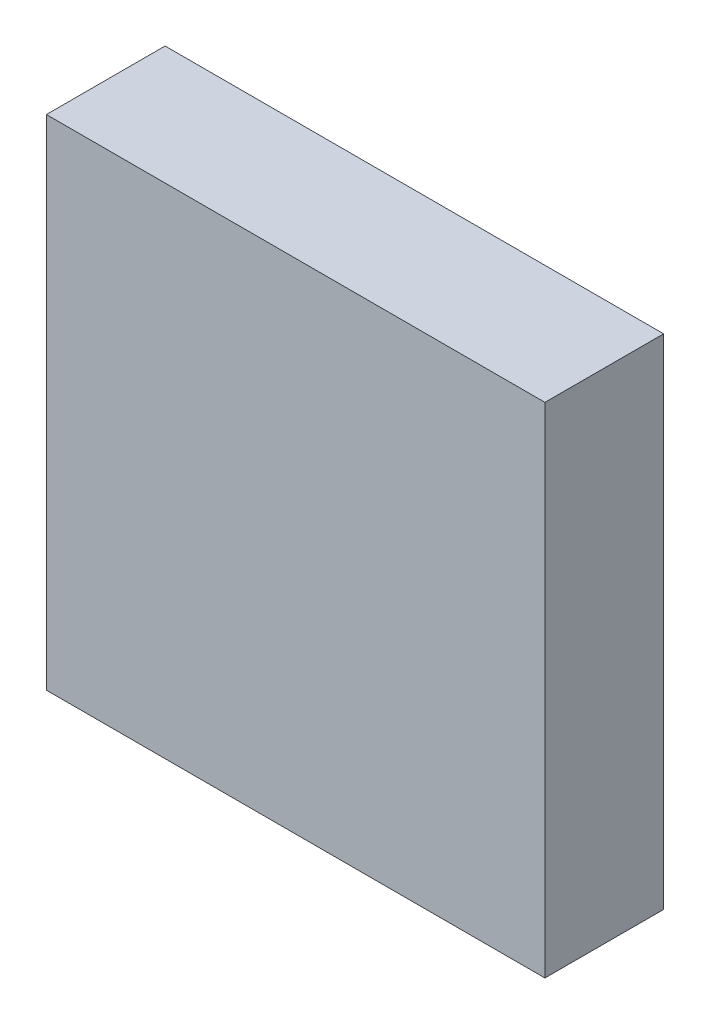
SolidWorks part; units mm, degrees
ref_plane "Front Plane" through (0, 0, 0) normal (0, 0, 1) x (1, 0, 0)
ref_plane "Top Plane" through (0, 0, 0) normal (0, 1, 0) x (1, 0, 0)
ref_plane "Right Plane" through (0, 0, 0) normal (1, 0, 0) x (0, 0, -1)
sketch "Sketch1" plane through (0, 0, 0) normal (0, 0, 1) x (1, 0, 0)
  line L1 (-1000, 1000) -> (1000, 1000)
  line L2 (-1000, 1000) -> (-1000, -1000)
  line L3 (-1000, -1000) -> (1000, -1000)
  line L4 (1000, 1000) -> (1000, -1000)
  line L5 (-1000, 1000) -> (1000, -1000) construction
  line L6 (-1000, -1000) -> (1000, 1000) construction
  line L7 (-1050, 1050) -> (1050, 1050)
  line L8 (-1050, 1050) -> (-1050, -1050)
  line L9 (-1050, -1050) -> (1050, -1050)
  line L10 (1050, 1050) -> (1050, -1050)
  line L11 (-1050, 1050) -> (1050, -1050) construction
  line L12 (-1050, -1050) -> (1050, 1050) construction
  point P0 (0, 0)
  point P6 (0, 0)
  dimension "D1" = 2000
  dimension "D2" = 2000
  dimension "D3" = 2100
  dimension "D4" = 2100
extrude "Boss-Extrude1" add sketch "Sketch1" along normal blind 500
sketch "Sketch2" plane through (0, 0, 500) normal (0, 0, 1) x (1, 0, 0)
  line L1 (-1050, 1050) -> (1050, 1050)
  line L2 (-1050, 1050) -> (-1050, -1050)
  line L3 (-1050, -1050) -> (1050, -1050)
  line L4 (1050, 1050) -> (1050, -1050)
  line L5 (-1050, 1050) -> (1050, -1050) construction
  line L6 (-1050, -1050) -> (1050, 1050) construction
  point P0 (0, 0)
extrude "Boss-Extrude2" add sketch "Sketch2" against normal blind 10
